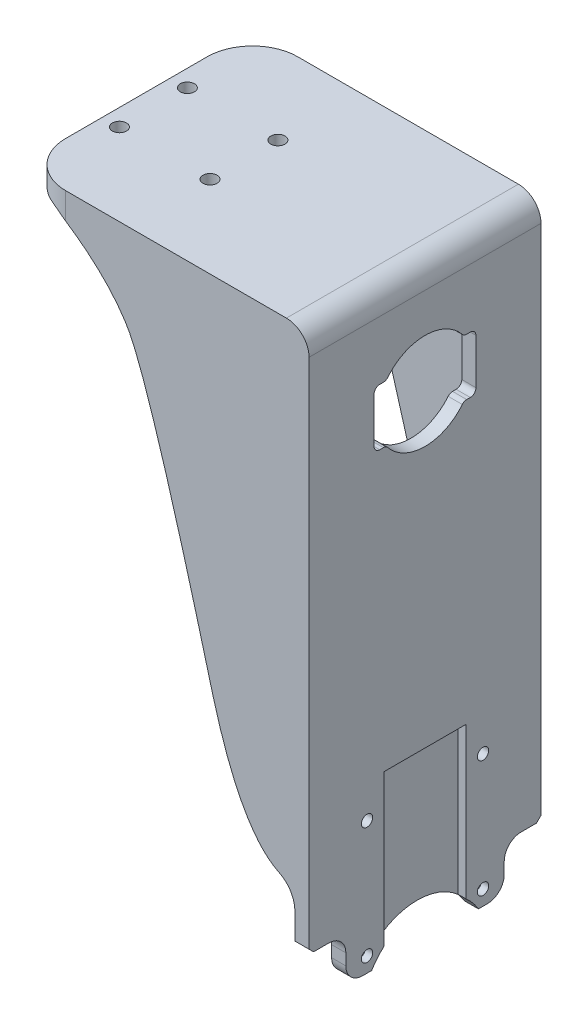
SolidWorks part; units mm, degrees
ref_plane "前视基准面" through (0, 0, 0) normal (0, 0, 1) x (1, 0, 0)
ref_plane "上视基准面" through (0, 0, 0) normal (0, 1, 0) x (1, 0, 0)
ref_plane "右视基准面" through (0, 0, 0) normal (1, 0, 0) x (0, 0, -1)
other "Configuration Table"
sketch "草图1" plane through (0, 0, 0) normal (0, 1, 0) x (1, 0, 0)
  line L0 (-22.5, 11.2328) -> (-22.5, -19.6928) construction
  line L1 (-25.5, 20.5) -> (25.5, 20.5)
  line L2 (-25.5, 20.5) -> (-25.5, -20.5)
  line L3 (-25.5, -20.5) -> (25.5, -20.5)
  line L4 (25.5, 20.5) -> (25.5, -20.5)
  line L5 (-25.5, 20.5) -> (25.5, -20.5) construction
  line L6 (-25.5, -20.5) -> (25.5, 20.5) construction
  line L7 (-17.7344, 0) -> (22.5332, 0) construction
  circle A0 centre (-22.5, 6) radius 1.25
  circle A1 centre (-22.5, -6) radius 1.25
  circle A2 centre (-6.5, 6) radius 1.25
  circle A3 centre (-6.5, -6) radius 1.25
  point P0 (0, 0)
  dimension "D3" = 2.5
  dimension "D4" = 12
  dimension "D6" = 16
  dimension "D7" = 2.5
  dimension "D1" = 41
  dimension "D2" = 3
  dimension "D5" = 51
extrude "凸台-拉伸1" add sketch "草图1" along normal blind 3.4
sketch "草图2" plane through (25.5, 0, 0) normal (1, 0, 0) x (0, 0, -1)
  line L0 (-20.5, 0) -> (20.5, 0)
  line L1 (20.5, 0) -> (20.5, -100)
  line L2 (20.5, -100) -> (9.4381, -100)
  line L3 (-20.5, -100) -> (-20.5, 0)
  line L4 (0, 12.0877) -> (0, -94.65) construction
  line L5 (-30.0581, -87) -> (27.3842, -87) construction
  line L6 (-9.4381, -100) -> (-20.5, -100)
  line L7 (0, -64) -> (0, -84.8169) construction
  circle A0 centre (-10.25, -97.35) radius 1
  circle A1 centre (10.25, -97.35) radius 1
  circle A2 centre (10.25, -76.65) radius 1
  circle A3 centre (-10.25, -76.65) radius 1
  arc A4 (9.4381, -100) -> (-9.4381, -100) centre (0, -105.65) ccw
  dimension "D3" = 2
  dimension "D4" = 20.5
  dimension "D5" = 20.7
  dimension "D6" = 8.3
  dimension "D7" = 11
  dimension "D1" = 100
  dimension "D2" = 13
extrude "凸台-拉伸2" add sketch "草图2" against normal blind 2.5
sketch "草图3" plane through (25.5, 0, 0) normal (1, 0, 0) x (0, 0, -1)
  line L0 (0, 9.7576) -> (0, -76.6891) construction
  line L5 (-7.25, -70.65) -> (-7.25, -106.3874)
  line L6 (-7.25, -106.3874) -> (7.25, -106.3874)
  line L7 (-7.25, -70.65) -> (7.25, -70.65)
  line L8 (7.25, -70.65) -> (7.25, -106.3874)
  circle A0 centre (-10.25, -76.65) radius 1 construction
  point P10 (0, -70.65)
  point P11 (0, -106.3874)
  dimension "D2" = 6
  dimension "D1" = 3
extrude "切除-拉伸1" cut sketch "草图3" against normal blind 1.4
sketch "草图5" plane through (0, 0, -20.5) normal (0, 0, -1) x (-1, 0, 0)
  line L0 (-25.5, 3.4) -> (19.5, 3.4)
  line L1 (-25.5, -82.805) -> (-25.5, 3.4)
  line L2 (19.5, 3.4) -> (19.5, 0)
  line L3 (-25.5, -82.805) -> (-23, -82.805)
  line L5 (-25.5, 3.4) -> (-25.5, -100) construction
  line L6 (25.5, 3.4) -> (25.5, 0) construction
  spline S0 degree 2 poles (19.5, 0) (10.6712, -5.3693) (2.7794, -18.1934) (-14.2375, -82.4755) (-23, -82.805) knots 0 0 0 0.396049 0.78858 1 1 1
  point P7 (-25.5, 3.4)
  dimension "D1" = 6
extrude "凸台-拉伸4" add sketch "草图5" against normal blind 2
mirror "镜向3" about plane through (0, 0, 0) normal (0, 0, 1) of "凸台-拉伸4"
fillet "圆角1" radius 8 2 edges at (-25.5, 1.7, -20.5) (-25.5, 1.7, 20.5)
fillet "圆角2" radius 4 2 edges at (23, 0, 0) (25.5, 3.4, 0)
sketch "草图6" plane through (23, 0, 0) normal (-1, 0, 0) x (0, 0, 1)
  circle A0 centre (10.25, -97.35) radius 2
  circle A1 centre (-10.25, -97.35) radius 2
  dimension "D1" = 4
  dimension "D2" = 4
extrude "切除-拉伸2" cut sketch "草图6" against normal blind 1.2
sketch "草图8" plane through (25.5, 0, 0) normal (1, 0, 0) x (0, 0, -1)
  line L0 (14, -102.818) -> (14, -92)
  line L1 (14, -92) -> (23.4685, -92)
  line L2 (23.4685, -92) -> (23.4685, -110.0082)
  line L3 (23.4685, -110.0082) -> (-23.4685, -110.0082)
  line L4 (-23.4685, -92) -> (-23.4685, -110.0082)
  line L5 (0, -27.3846) -> (0, -80.1854) construction
  line L6 (-14, -92) -> (-23.4685, -92)
  line L7 (-14, -102.818) -> (-14, -92)
  line L8 (-14, -102.818) -> (14, -102.818)
  line L9 (9.4381, -100) -> (20.5, -100) construction
  point P9 (0, -110.0082)
  dimension "D1" = 28
  dimension "D2" = 8
extrude "切除-拉伸3" cut sketch "草图8" against normal blind 4
fillet "圆角3" radius 3 4 edges at (24.25, -100, -14) (24.25, -92, -14) (24.25, -92, 14) (24.25, -100, 14)
sketch "草图9" plane through (23, 0, 0) normal (-1, 0, 0) x (0, 0, 1)
  line L0 (0, 14.9311) -> (0, -25.9548) construction
  circle A0 centre (10.25, -76.65) radius 2
  circle A1 centre (-10.25, -76.65) radius 2
  dimension "D1" = 4
extrude "切除-拉伸4" cut sketch "草图9" against normal blind 0.8
sketch "草图10" plane through (0, 0, 0) normal (0, -1, 0) x (-1, 0, 0)
  line L0 (28.9726, 0) -> (-5.0372, 0) construction
  line L1 (6.5, -6) -> (22.5, -6) construction
  line L2 (14.5, -8.9106) -> (14.5, 10.615) construction
  circle A0 centre (6.5, -6) radius 2.5
  circle A2 centre (22.5, -6) radius 2.5
  circle A3 centre (6.5, 6) radius 2.5
  circle A4 centre (22.5, 6) radius 2.5
  dimension "D1" = 5
extrude "切除-拉伸5" cut sketch "草图10" against normal blind 1.4
chamfer "倒角1" distance 0.8 angle 45 2 edges at (24.25, -92, 20.5) (24.25, -92, -20.5)
fillet "圆角4" radius 4 6 edges at (-0.25, 0, -18.5) (21.8284, -1.1716, -18.5) (-0.25, 0, 18.5) (21.8284, -1.1716, 18.5) (23, -43.4025, -18.5) (23, -43.4025, 18.5)
fillet "圆角5" radius 5 4 edges at (23, -82.805, 17.5) (23, -82.805, -17.5) (-19.5, 0, 17.373) (-19.5, 0, -17.373)
sketch "草图12" plane through (23, 0, 0) normal (-1, 0, 0) x (0, 0, 1)
  line L0 (-6.8739, -11) -> (-9, -11)
  line L1 (9, -21) -> (6.8739, -21)
  line L2 (9, -21) -> (9, -11)
  line L3 (9, -11) -> (6.8739, -11)
  line L4 (-9, -21) -> (-9, -11)
  line L5 (9, -21) -> (-9, -11) construction
  line L6 (9, -11) -> (-9, -21) construction
  line L7 (-6.8739, -21) -> (-9, -21)
  line L8 (-12.5, 0) -> (12.5, 0) construction
  arc A0 (-6.8739, -21) -> (6.8739, -21) centre (0, -16) ccw
  arc A1 (6.8739, -11) -> (-6.8739, -11) centre (0, -16) ccw
  point P6 (0, 0)
  dimension "D1" = 8.5
  dimension "D2" = 10
  dimension "D3" = 18
  dimension "D4" = 16
extrude "切除-拉伸6" cut sketch "草图12" against normal blind 10
fillet "圆角6" radius 1 8 edges at (24.25, -11, 6.8739) (24.25, -11, 9) (24.25, -11, -6.8739) (24.25, -11, -9) (24.25, -21, -9) (24.25, -21, -6.8739) (24.25, -21, 6.8739) (24.25, -21, 9)
